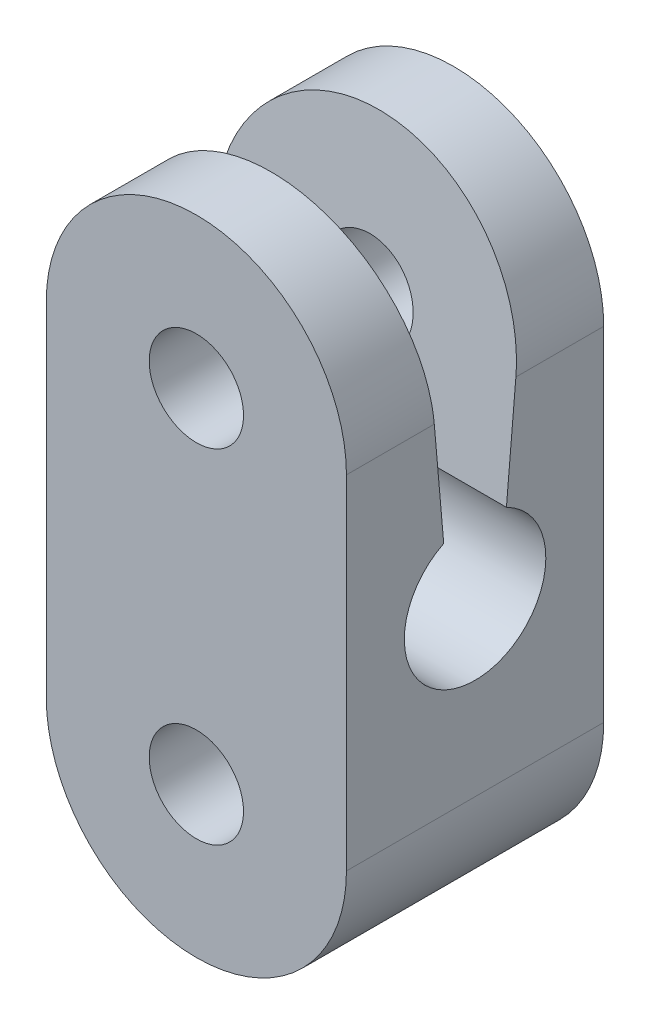
SolidWorks part; units mm, degrees
ref_plane "前视基准面" through (0, 0, 0) normal (0, 0, 1) x (1, 0, 0)
ref_plane "上视基准面" through (0, 0, 0) normal (0, 1, 0) x (1, 0, 0)
ref_plane "右视基准面" through (0, 0, 0) normal (1, 0, 0) x (0, 0, -1)
sketch "草图1" plane through (0, 0, 0) normal (0, 0, 1) x (1, 0, 0)
  line L0 (0, -4) -> (0, 4) construction
  line L1 (-3.5, -4) -> (-3.5, 4)
  line L2 (3.5, -4) -> (3.5, 4)
  arc A0 (-3.5, -4) -> (3.5, -4) centre (0, -4) ccw
  arc A1 (3.5, 4) -> (-3.5, 4) centre (0, 4) ccw
  point P2 (0, 0)
  dimension "D1" = 7
  dimension "D2" = 8
extrude "凸台-拉伸1" add sketch "草图1" along normal mid plane 6
sketch "草图2" plane through (3.5, 0, 0) normal (1, 0, 0) x (0, 0, -1)
  line L0 (0, 0) -> (0, 3.8562) construction
  line L1 (-0.731, 1.4792) -> (-1.4053, 9.1866)
  line L2 (-1.4053, 9.1866) -> (1.4053, 9.1866)
  line L4 (0, 1.4792) -> (-0.731, 1.4792)
  line L5 (0, 1.4792) -> (0.731, 1.4792)
  line L6 (0.731, 1.4792) -> (1.4053, 9.1866)
  circle A0 centre (0, 0) radius 1.65
  dimension "D1" = 3.3
  dimension "D2" = 10
extrude "切除-拉伸2" cut sketch "草图2" against normal blind 23
sketch "草图3" plane through (0, 0, 3) normal (0, 0, 1) x (1, 0, 0)
  circle A0 centre (0, 4) radius 1.1
  dimension "D1" = 2.2
extrude "切除-拉伸3" cut sketch "草图3" against normal blind 23
sketch "草图4" plane through (0, 0, 3) normal (0, 0, 1) x (1, 0, 0)
  circle A0 centre (0, -4) radius 1.1
  dimension "D1" = 2.2
extrude "切除-拉伸4" cut sketch "草图4" against normal blind 23
